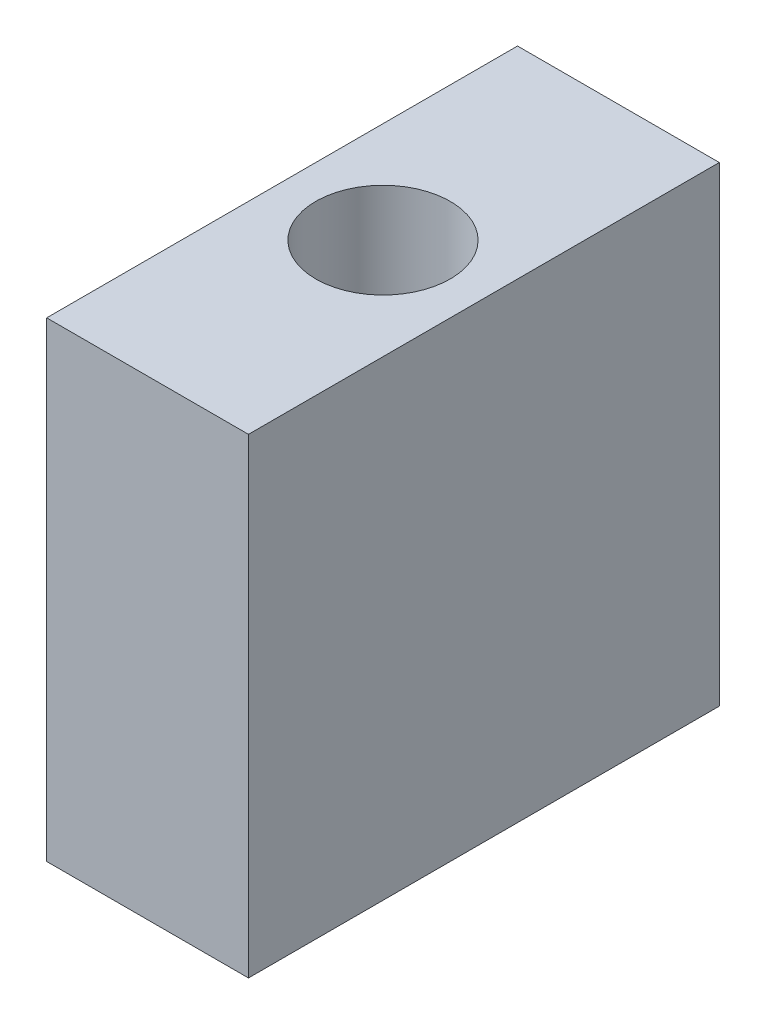
SolidWorks part; units mm, degrees
ref_plane "Front Plane" through (0, 0, 0) normal (0, 0, 1) x (1, 0, 0)
ref_plane "Top Plane" through (0, 0, 0) normal (0, 1, 0) x (1, 0, 0)
ref_plane "Right Plane" through (0, 0, 0) normal (1, 0, 0) x (0, 0, -1)
sketch "Sketch1" plane through (0, 0, 0) normal (0, 1, 0) x (1, 0, 0)
  line L1 (-1.5, 3.5) -> (1.5, 3.5)
  line L2 (-1.5, 3.5) -> (-1.5, -3.5)
  line L3 (-1.5, -3.5) -> (1.5, -3.5)
  line L4 (1.5, 3.5) -> (1.5, -3.5)
  line L5 (-1.5, 3.5) -> (1.5, -3.5) construction
  line L6 (-1.5, -3.5) -> (1.5, 3.5) construction
  circle A0 centre (0, 0) radius 1
  point P0 (0, 0)
extrude "Boss-Extrude1" add sketch "Sketch1" along normal blind 7
